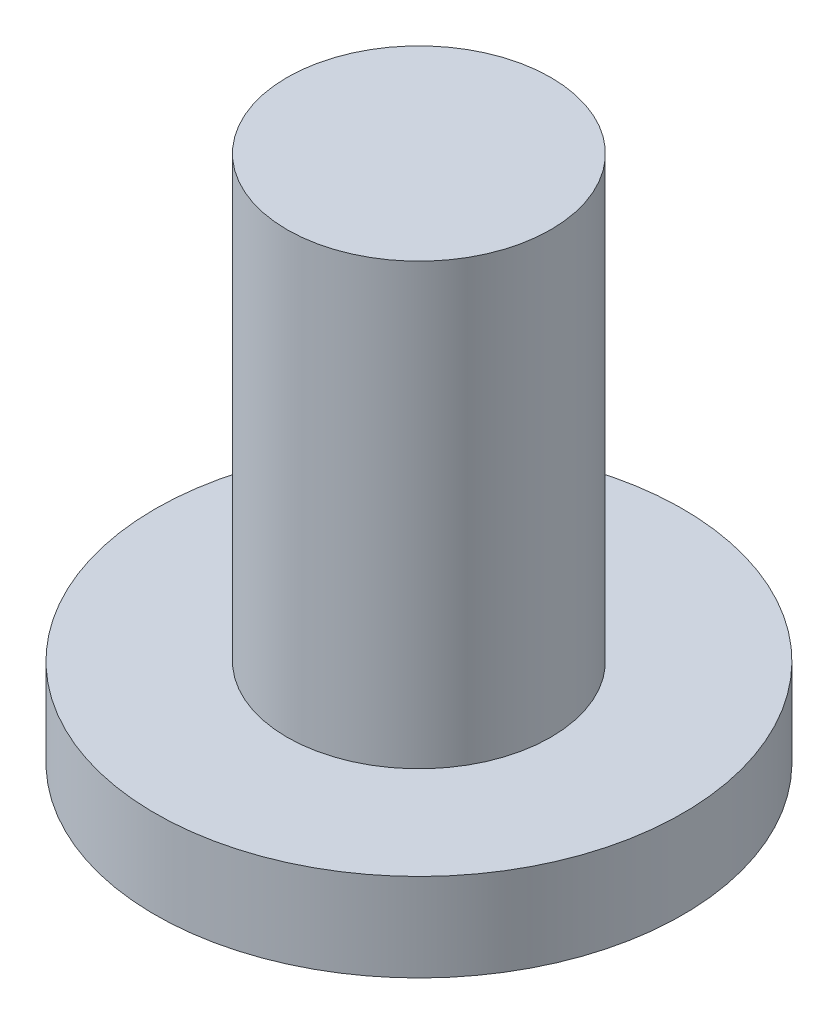
SolidWorks part; units mm, degrees
ref_plane "Front Plane" through (0, 0, 0) normal (0, 0, 1) x (1, 0, 0)
ref_plane "Top Plane" through (0, 0, 0) normal (0, 1, 0) x (1, 0, 0)
ref_plane "Right Plane" through (0, 0, 0) normal (1, 0, 0) x (0, 0, -1)
sketch "Sketch1" plane through (0, 0, 0) normal (0, 0, 1) x (1, 0, 0)
  line L0 (0, 0) -> (-6, 0)
  line L1 (-6, 0) -> (-6, 2)
  line L2 (-6, 2) -> (-3, 2)
  line L3 (-3, 2) -> (-3, 12)
  line L4 (-3, 12) -> (0, 12)
  line L5 (0, 12) -> (0, 0)
  dimension "D1" = 2
  dimension "D2" = 12
  dimension "D3" = 3
  dimension "D4" = 6
revolve "Revolve1" add sketch "Sketch1" angle 360 about L5
